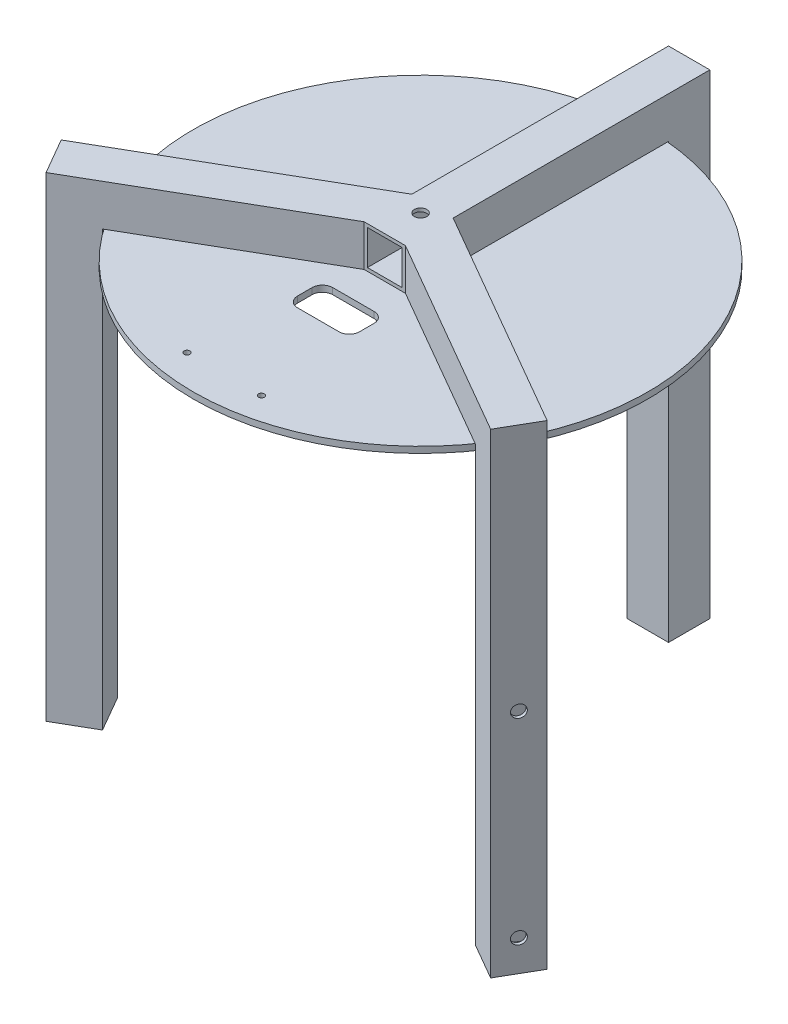
SolidWorks part; units mm, degrees
ref_plane "Front Plane" through (0, 0, 0) normal (0, 0, 1) x (1, 0, 0)
ref_plane "Top Plane" through (0, 0, 0) normal (0, 1, 0) x (1, 0, 0)
ref_plane "Right Plane" through (0, 0, 0) normal (1, 0, 0) x (0, 0, -1)
sketch "Sketch1" plane through (0, 0, 0) normal (0, 1, 0) x (1, 0, 0)
  line L0 (0, 0) -> (43249.443, -24970.0776) construction
  line L1 (-10, 130) -> (10, 130)
  line L2 (-10, 130) -> (-10, 5.7735)
  line L3 (-10, -17.3205) -> (10, -17.3205)
  line L4 (10, 130) -> (10, 5.7735)
  line L5 (10, -17.3205) -> (107.5833, -73.6603)
  line L7 (10, 5.7735) -> (117.5833, -56.3397)
  line L8 (107.5833, -73.6603) -> (117.5833, -56.3397)
  line L9 (0, 0) -> (43301.2702, 25000) construction
  line L11 (-117.5833, -56.3397) -> (-10, 5.7735)
  line L12 (-117.5833, -56.3397) -> (-107.5833, -73.6603)
  line L13 (-107.5833, -73.6603) -> (-10, -17.3205)
  circle A0 centre (0, 0) radius 110 construction
  point P7 (0, 130)
  point P15 (112.5833, -65)
  point P21 (-112.5833, -65)
  dimension "D1" = 220
  dimension "D2" = 20
  dimension "D3" = 130
  dimension "D4" = 20
  dimension "D5" = 130
  dimension "D6" = 120
  dimension "D7" = 120
  dimension "D8" = 130
  dimension "D9" = 20
extrude "Boss-Extrude1" add sketch "Sketch1" along normal blind 20
sketch "Sketch2" plane through (112.5833, 0, 65) normal (0.866, 0, 0.5) x (0.5, 0, -0.866)
  line L0 (-8.4, 18.4) -> (-8.4, 1.6)
  line L1 (-8.4, 1.6) -> (8.4, 1.6)
  line L2 (8.4, 1.6) -> (8.4, 18.4)
  line L3 (8.4, 18.4) -> (-8.4, 18.4)
  line L4 (-10, 0) -> (10, 0)
  line L5 (10, 0) -> (10, 20)
  line L6 (10, 20) -> (-10, 20)
  line L7 (-10, 20) -> (-10, 0)
  line L8 (-10, 0) -> (10, 0) construction
  line L9 (10, 0) -> (10, 20) construction
  line L10 (10, 20) -> (-10, 20) construction
  line L11 (-10, 20) -> (-10, 0) construction
  dimension "D1" = 0
  dimension "D2" = 1.6
extrude "Cut-Extrude1" cut sketch "Sketch2" against normal up to surface (123.3027 mm away)
sketch "Sketch3" plane through (0, 0, -130) normal (0, 0, -1) x (-1, 0, 0)
  line L0 (-8.4, 1.6) -> (8.4, 1.6)
  line L1 (8.4, 1.6) -> (8.4, 18.4)
  line L2 (8.4, 18.4) -> (-8.4, 18.4)
  line L3 (-8.4, 18.4) -> (-8.4, 1.6)
  line L4 (-10, 0) -> (10, 0)
  line L5 (10, 0) -> (10, 20)
  line L6 (10, 20) -> (-10, 20)
  line L7 (-10, 20) -> (-10, 0)
  line L8 (-10, 0) -> (10, 0) construction
  line L9 (10, 0) -> (10, 20) construction
  line L10 (10, 20) -> (-10, 20) construction
  line L11 (-10, 20) -> (-10, 0) construction
  dimension "D1" = 0
  dimension "D2" = 1.6
extrude "Cut-Extrude2" cut sketch "Sketch3" against normal up to surface (147.3205 mm away) up to face at (0, 10, 17.3205)
sketch "Sketch4" plane through (-112.5833, 0, 65) normal (-0.866, 0, 0.5) x (0.5, 0, 0.866)
  line L0 (-8.4, 1.6) -> (8.4, 1.6)
  line L1 (8.4, 1.6) -> (8.4, 18.4)
  line L2 (8.4, 18.4) -> (-8.4, 18.4)
  line L3 (-8.4, 18.4) -> (-8.4, 1.6)
  line L4 (-10, 0) -> (10, 0)
  line L5 (10, 0) -> (10, 20)
  line L6 (10, 20) -> (-10, 20)
  line L7 (-10, 20) -> (-10, 0)
  line L8 (-10, 0) -> (10, 0) construction
  line L9 (10, 0) -> (10, 20) construction
  line L10 (10, 20) -> (-10, 20) construction
  line L11 (-10, 20) -> (-10, 0) construction
  dimension "D1" = 0
  dimension "D2" = 1.6
extrude "Cut-Extrude4" cut sketch "Sketch4" against normal up to surface (113.6033 mm away)
sketch "Sketch5" plane through (-10, 0, 0) normal (-1, 0, 0) x (0, 0, 1)
  line L0 (-130, 20) -> (-110, 0)
  line L1 (-130, 0) -> (-5.7735, 0) construction
  line L2 (-110, 0) -> (-130, 0)
  line L3 (-130, 0) -> (-130, 20)
  dimension "D1" = 45
extrude "Cut-Extrude5" cut sketch "Sketch5" against normal up to surface (20 mm away) up to face at (10, 10, -67.8868)
sketch "Sketch6" plane through (-5, 0, -8.6603) normal (-0.5, 0, -0.866) x (-0.866, 0, 0.5)
  line L0 (130, 20) -> (110, 0)
  line L1 (5.7735, 0) -> (130, 0) construction
  line L2 (110, 0) -> (130, 0)
  line L3 (130, 0) -> (130, 20)
  dimension "D1" = 45
extrude "Cut-Extrude6" cut sketch "Sketch6" against normal up to surface (20 mm away) up to face at (-58.7917, 10, 45.4904)
sketch "Sketch7" plane through (-5, 0, 8.6603) normal (-0.5, 0, 0.866) x (0.866, 0, 0.5)
  line L0 (130, 20) -> (130, 0)
  line L1 (130, 0) -> (110, 0)
  line L2 (17.3205, 0) -> (130, 0) construction
  line L3 (110, 0) -> (130, 20)
  dimension "D1" = 45
extrude "Cut-Extrude7" cut sketch "Sketch7" against normal up to surface (20 mm away) up to face at (63.7917, 10, 25.2831)
sketch "Sketch8" plane through (-5, 0, 8.6603) normal (-0.5, 0, 0.866) x (0.866, 0, 0.5)
  line L0 (130, 20) -> (130, -210)
  line L1 (130, -210) -> (110, -210)
  line L2 (110, -210) -> (110, 0)
  line L3 (110, 0) -> (130, 20)
  dimension "D1" = 20
  dimension "D2" = 230
extrude "Boss-Extrude2" add sketch "Sketch8" against normal up to surface (20 mm away) up to face at (59.4615, 10, 22.7831)
sketch "Sketch9" plane through (0, -210, 0) normal (0, -1, 0) x (1, 0, 0)
  line L0 (100.8484, 48.5254) -> (115.3977, 56.9254)
  line L1 (115.3977, 56.9254) -> (106.9977, 71.4746)
  line L2 (106.9977, 71.4746) -> (92.4484, 63.0746)
  line L3 (92.4484, 63.0746) -> (100.8484, 48.5254)
  line L4 (100.2628, 46.3397) -> (117.5833, 56.3397)
  line L5 (117.5833, 56.3397) -> (107.5833, 73.6603)
  line L6 (107.5833, 73.6603) -> (90.2628, 63.6603)
  line L7 (90.2628, 63.6603) -> (100.2628, 46.3397)
  line L8 (100.2628, 46.3397) -> (117.5833, 56.3397) construction
  line L9 (117.5833, 56.3397) -> (107.5833, 73.6603) construction
  line L10 (107.5833, 73.6603) -> (90.2628, 63.6603) construction
  line L11 (90.2628, 63.6603) -> (100.2628, 46.3397) construction
  dimension "D1" = 0
  dimension "D2" = 1.6
extrude "Cut-Extrude8" cut sketch "Sketch9" against normal offset from surface (228.4 mm away) 1.6 up to face at (0, 20, 2.3094)
sketch "Sketch10" plane through (10, 0, 0) normal (1, 0, 0) x (0, 0, -1)
  line L0 (130, 20) -> (130, -210)
  line L1 (130, -210) -> (110, -210)
  line L2 (110, -210) -> (110, 0)
  line L3 (110, 0) -> (130, 20)
  line L4 (-56.3397, -210) -> (-73.6603, -210) construction
  dimension "D1" = 20
extrude "Boss-Extrude3" add sketch "Sketch10" against normal up to surface (20 mm away) up to face at (-10, 10, -62.8868)
sketch "Sketch11" plane through (0, -210, 0) normal (0, -1, 0) x (1, 0, 0)
  line L0 (-8.4, -111.6) -> (-8.4, -128.4)
  line L1 (-8.4, -128.4) -> (8.4, -128.4)
  line L2 (8.4, -128.4) -> (8.4, -111.6)
  line L3 (8.4, -111.6) -> (-8.4, -111.6)
  line L4 (-10, -110) -> (-10, -130)
  line L5 (-10, -130) -> (10, -130)
  line L6 (10, -130) -> (10, -110)
  line L7 (10, -110) -> (-10, -110)
  line L8 (-10, -110) -> (-10, -130) construction
  line L9 (-10, -130) -> (10, -130) construction
  line L10 (10, -130) -> (10, -110) construction
  line L11 (10, -110) -> (-10, -110) construction
  dimension "D1" = 0
  dimension "D2" = 1.6
extrude "Cut-Extrude9" cut sketch "Sketch11" against normal offset from surface (228.4 mm away) 1.6 up to face at (0, 20, 2.3094)
sketch "Sketch12" plane through (-5, 0, -8.6603) normal (-0.5, 0, -0.866) x (-0.866, 0, 0.5)
  line L0 (130, 20) -> (130, -210)
  line L1 (130, -210) -> (110, -210)
  line L2 (110, -210) -> (110, 0)
  line L3 (110, 0) -> (130, 20)
  line L4 (-56.3397, -210) -> (-73.6603, -210) construction
  dimension "D1" = 20
extrude "Boss-Extrude4" add sketch "Sketch12" against normal up to surface (20 mm away) up to face at (-54.4615, 10, 42.9904)
sketch "Sketch13" plane through (0, -210, 0) normal (0, -1, 0) x (1, 0, 0)
  line L0 (-92.4484, 63.0746) -> (-106.9977, 71.4746)
  line L1 (-106.9977, 71.4746) -> (-115.3977, 56.9254)
  line L2 (-115.3977, 56.9254) -> (-100.8484, 48.5254)
  line L3 (-100.8484, 48.5254) -> (-92.4484, 63.0746)
  line L4 (-90.2628, 63.6603) -> (-107.5833, 73.6603)
  line L5 (-107.5833, 73.6603) -> (-117.5833, 56.3397)
  line L6 (-117.5833, 56.3397) -> (-100.2628, 46.3397)
  line L7 (-100.2628, 46.3397) -> (-90.2628, 63.6603)
  line L8 (-90.2628, 63.6603) -> (-107.5833, 73.6603) construction
  line L9 (-107.5833, 73.6603) -> (-117.5833, 56.3397) construction
  line L10 (-117.5833, 56.3397) -> (-100.2628, 46.3397) construction
  line L11 (-100.2628, 46.3397) -> (-90.2628, 63.6603) construction
  dimension "D1" = 0
  dimension "D2" = 1.6
extrude "Cut-Extrude10" cut sketch "Sketch13" against normal offset from surface (228.4 mm away) 1.6 up to face at (0, 20, 2.3094)
sketch "Sketch14" plane through (-112.5833, 0, 65) normal (-0.866, 0, 0.5) x (0.5, 0, 0.866)
  line L0 (10, -210) -> (-10, -210) construction
  circle A0 centre (0, -100) radius 3
  circle A1 centre (0, -195) radius 3
  point P4 (0, -210)
  point P5 (0, -210)
  dimension "D1" = 6
  dimension "D3" = 6
  dimension "D2" = 110
  dimension "D4" = 95
extrude "Cut-Extrude11" cut sketch "Sketch14" against normal up to next
sketch "Sketch15" plane through (0, 0, -130) normal (0, 0, -1) x (-1, 0, 0)
  line L0 (10, -210) -> (-10, -210) construction
  circle A0 centre (0, -100) radius 3
  circle A1 centre (0, -195) radius 3
  point P4 (0, -210)
  dimension "D1" = 6
  dimension "D3" = 6
  dimension "D2" = 110
  dimension "D4" = 95
extrude "Cut-Extrude12" cut sketch "Sketch15" against normal up to next
sketch "Sketch16" plane through (112.5833, 0, 65) normal (0.866, 0, 0.5) x (0.5, 0, -0.866)
  line L0 (10, -210) -> (-10, -210) construction
  circle A0 centre (0, -100) radius 3
  circle A1 centre (0, -195) radius 3
  point P4 (0, -210)
  point P5 (0, -210)
  dimension "D1" = 6
  dimension "D3" = 6
  dimension "D2" = 110
  dimension "D4" = 95
extrude "Cut-Extrude13" cut sketch "Sketch16" against normal up to next
sketch "Sketch17" plane through (0, 0, 0) normal (0, -1, 0) x (1, 0, 0)
  line L0 (100.2628, 46.3397) -> (90.2628, 63.6603) construction
  circle A0 centre (0, 0) radius 110
extrude "Boss-Extrude6" add sketch "Sketch17" along normal blind 3 separate body
sketch "Sketch18" plane through (0, 20, 0) normal (0, 1, 0) x (1, 0, 0)
  circle A0 centre (0, 0) radius 3
  dimension "D1" = 6
extrude "Cut-Extrude14" cut sketch "Sketch18" against normal up to next (1.6 mm away)
sketch "Sketch19" plane through (0, 1.6, 0) normal (0, 1, 0) x (1, 0, 0)
  circle A0 centre (0, 0) radius 1.425
  dimension "D1" = 2.85
extrude "Cut-Extrude15" cut sketch "Sketch19" against normal up to surface (4.6 mm away)
sketch "Sketch20" plane through (0, 0, 0) normal (0, 1, 0) x (1, 0, 0)
  line L0 (-43.2235, -95) -> (49956.7765, -95) construction
  line L1 (-10, -17.3205) -> (10, -17.3205) construction
  line L2 (0, 0) -> (0, -50000) construction
  line L3 (-45.2259, -41) -> (49954.7741, -41) construction
  line L5 (-10, -32.5) -> (10, -32.5)
  line L6 (-15, -37.5) -> (-15, -44.5)
  line L7 (-10, -49.5) -> (10, -49.5)
  line L8 (15, -37.5) -> (15, -44.5)
  circle A0 centre (18, -95) radius 1.425
  circle A1 centre (-18, -95) radius 1.425
  arc A2 (15, -37.5) -> (10, -32.5) centre (10, -37.5) ccw
  arc A3 (10, -49.5) -> (15, -44.5) centre (10, -44.5) ccw
  arc A4 (-10, -49.5) -> (-15, -44.5) centre (-10, -44.5) cw
  arc A5 (-15, -37.5) -> (-10, -32.5) centre (-10, -37.5) cw
  point P18 (15, -41)
  point P19 (0, -32.5)
  point P22 (15, -32.5)
  point P25 (15, -49.5)
  point P28 (-15, -49.5)
  dimension "D2" = 2.85
  dimension "D7" = 5
  dimension "D1" = 95
  dimension "D3" = 36
  dimension "D4" = 41
  dimension "D5" = 30
  dimension "D6" = 17
extrude "Cut-Extrude16" cut sketch "Sketch20" against normal up to next (3 mm away)
